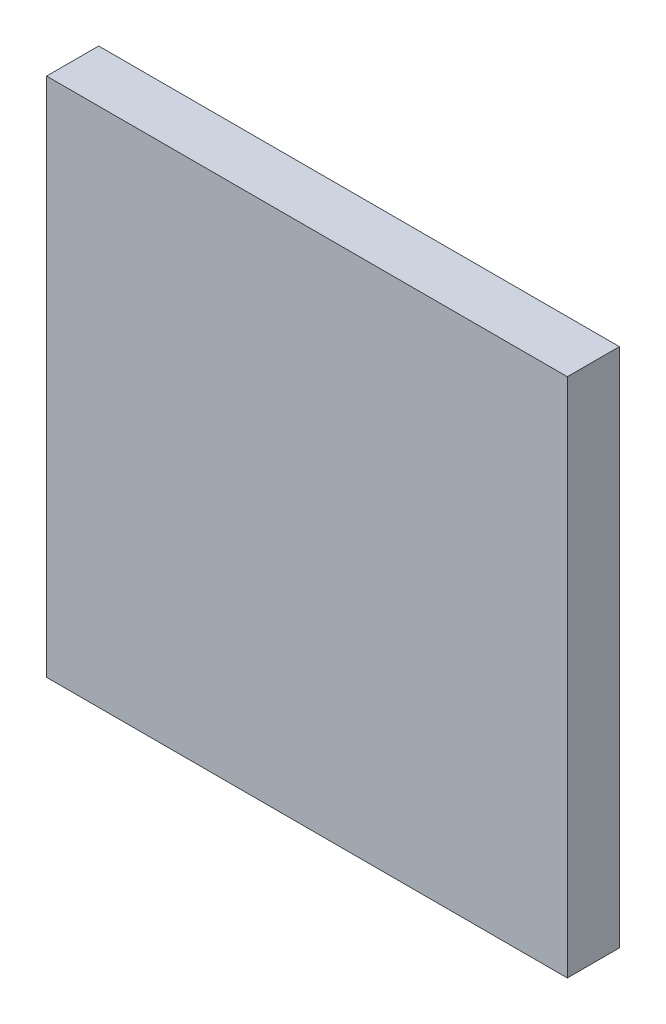
SolidWorks part; units mm, degrees
ref_plane "前视基准面" through (0, 0, 0) normal (0, 0, 1) x (1, 0, 0)
ref_plane "上视基准面" through (0, 0, 0) normal (0, 1, 0) x (1, 0, 0)
ref_plane "右视基准面" through (0, 0, 0) normal (1, 0, 0) x (0, 0, -1)
other "Configuration Table"
sketch "草图1" plane through (0, 0, 0) normal (0, 0, 1) x (1, 0, 0)
  line L1 (-50, -50) -> (50, -50)
  line L2 (-50, -50) -> (-50, 50)
  line L3 (-50, 50) -> (50, 50)
  line L4 (50, -50) -> (50, 50)
  line L5 (-50, -50) -> (50, 50) construction
  line L6 (-50, 50) -> (50, -50) construction
  point P0 (0, 0)
extrude "凸台-拉伸1" add sketch "草图1" along normal blind 10
